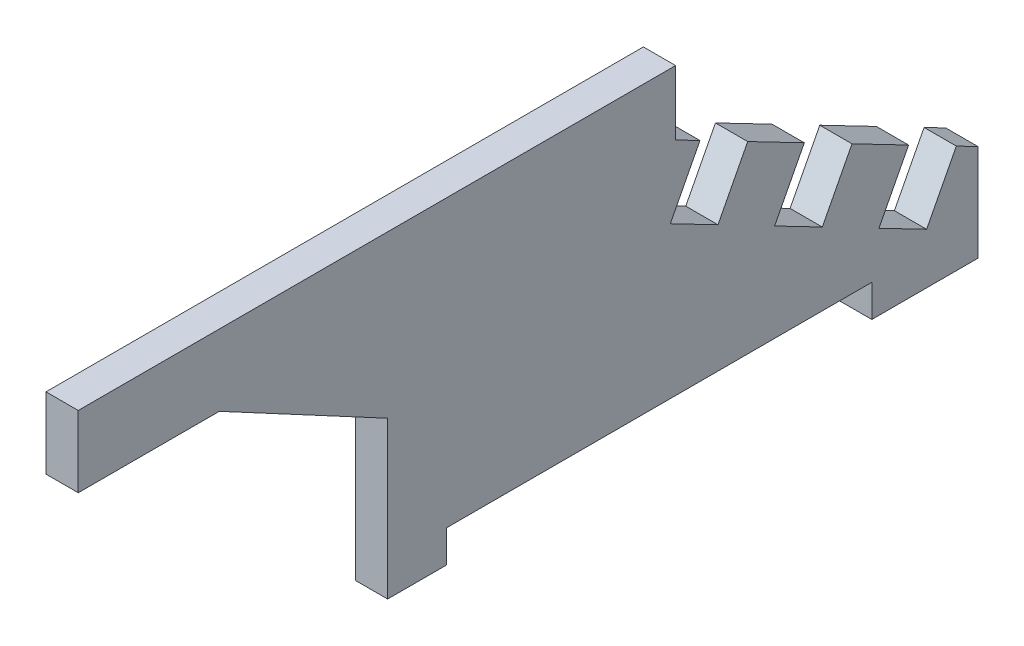
SolidWorks part; units mm, degrees
ref_plane "Front Plane" through (0, 0, 0) normal (0, 0, 1) x (1, 0, 0)
ref_plane "Top Plane" through (0, 0, 0) normal (0, 1, 0) x (1, 0, 0)
ref_plane "Right Plane" through (0, 0, 0) normal (1, 0, 0) x (0, 0, -1)
sketch "Sketch1" plane through (0, 0, 0) normal (1, 0, 0) x (0, 0, -1)
  line L0 (-23.4056, -13.3287) -> (32.1928, -13.3287)
  line L1 (32.1928, -13.3287) -> (32.1928, -19.3287)
  line L2 (60.3362, -33.9291) -> (60.3362, -39.9291)
  line L3 (50.4545, -39.9291) -> (10.85, -39.9291)
  line L4 (5.3873, -39.9291) -> (5.3873, -28.3527)
  line L5 (32.1928, -19.3287) -> (34.4623, -20.5061)
  line L6 (5.3873, -28.3527) -> (-10.2782, -19.9656)
  line L7 (27.6739, -39.9291) -> (27.6739, -13.3287) construction
  line L8 (-10.2782, -19.9656) -> (-23.4056, -19.9656)
  line L9 (-23.4056, -19.9656) -> (-23.4056, -13.3287)
  line L11 (58.3182, -32.8821) -> (60.3362, -33.9291)
  line L12 (5.3873, -39.9291) -> (5.3873, -42.9291)
  line L13 (5.3873, -42.9291) -> (10.85, -42.9291)
  line L14 (10.85, -39.9291) -> (10.85, -42.9291)
  line L15 (48.6094, -27.8454) -> (53.8799, -30.5796)
  line L16 (50.4545, -39.9291) -> (50.4545, -42.9291)
  line L17 (50.4545, -42.9291) -> (60.3362, -42.9291)
  line L18 (60.3362, -39.9291) -> (60.3362, -42.9291)
  line L19 (34.4623, -20.5061) -> (31.6993, -25.832)
  line L20 (38.9006, -22.8086) -> (36.1376, -28.1346)
  line L21 (31.6993, -25.832) -> (36.1376, -28.1346)
  line L22 (38.9006, -22.8086) -> (44.1711, -25.5429)
  line L23 (44.1711, -25.5429) -> (41.4081, -30.8688)
  line L24 (48.6094, -27.8454) -> (45.8464, -33.1713)
  line L25 (41.4081, -30.8688) -> (45.8464, -33.1713)
  line L27 (53.8799, -30.5796) -> (51.1169, -35.9056)
  line L28 (58.3182, -32.8821) -> (55.5552, -38.2081)
  line L29 (51.1169, -35.9056) -> (55.5552, -38.2081)
  line L30 (51.1169, -35.9056) -> (45.8464, -33.1713) construction
  line L31 (41.4081, -30.8688) -> (36.1376, -28.1346) construction
  dimension "D1" = 2.5567
  dimension "D2" = 5.9375
  dimension "D3" = 2.2734
  dimension "D4" = 28.1434
extrude "Boss-Extrude1" add sketch "Sketch1" along normal blind 3
